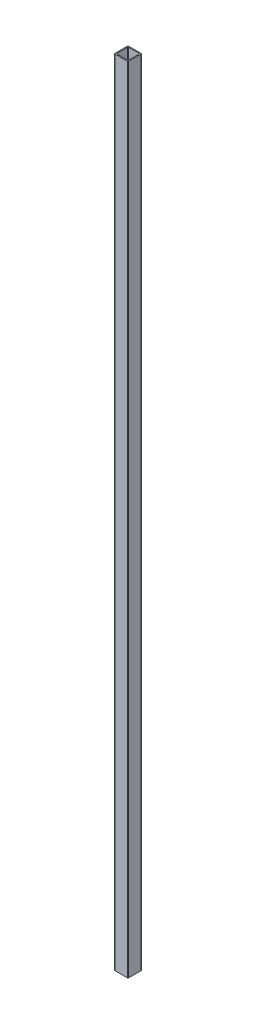
SolidWorks part; units mm, degrees
ref_plane "Front Plane" through (0, 0, 0) normal (0, 0, 1) x (1, 0, 0)
ref_plane "Top Plane" through (0, 0, 0) normal (0, 1, 0) x (1, 0, 0)
ref_plane "Right Plane" through (0, 0, 0) normal (1, 0, 0) x (0, 0, -1)
sketch "Sketch1" plane through (0, 0, 0) normal (0, 1, 0) x (1, 0, 0)
  line L1 (-9, -10) -> (9, -10)
  line L2 (-10, -9) -> (-10, 9)
  line L3 (-9, 10) -> (9, 10)
  line L4 (10, -9) -> (10, 9)
  line L5 (-10, -10) -> (10, 10) construction
  line L6 (-10, 10) -> (10, -10) construction
  line L7 (-7.5, -8.5) -> (7.5, -8.5)
  line L8 (-8.5, -7.5) -> (-8.5, 7.5)
  line L9 (-7.5, 8.5) -> (7.5, 8.5)
  line L10 (8.5, -7.5) -> (8.5, 7.5)
  line L11 (-8.5, -8.5) -> (8.5, 8.5) construction
  line L12 (-8.5, 8.5) -> (8.5, -8.5) construction
  arc A0 (-9, -10) -> (-10, -9) centre (-9, -9) cw
  arc A1 (9, 10) -> (10, 9) centre (9, 9) cw
  arc A2 (9, -10) -> (10, -9) centre (9, -9) ccw
  arc A3 (-10, 9) -> (-9, 10) centre (-9, 9) cw
  arc A4 (-7.5, -8.5) -> (-8.5, -7.5) centre (-7.5, -7.5) cw
  arc A5 (7.5, -8.5) -> (8.5, -7.5) centre (7.5, -7.5) ccw
  arc A6 (7.5, 8.5) -> (8.5, 7.5) centre (7.5, 7.5) cw
  arc A7 (-8.5, 7.5) -> (-7.5, 8.5) centre (-7.5, 7.5) cw
  point P0 (0, 0)
  point P18 (0, 0)
  dimension "D3" = 1
  dimension "D6" = 1
  dimension "D7" = 1
  dimension "D8" = 1
  dimension "D9" = 1
  dimension "D1" = 20
  dimension "D2" = 20
  dimension "D4" = 17
  dimension "D5" = 17
extrude "Boss-Extrude1" add sketch "Sketch1" along normal blind 1160
